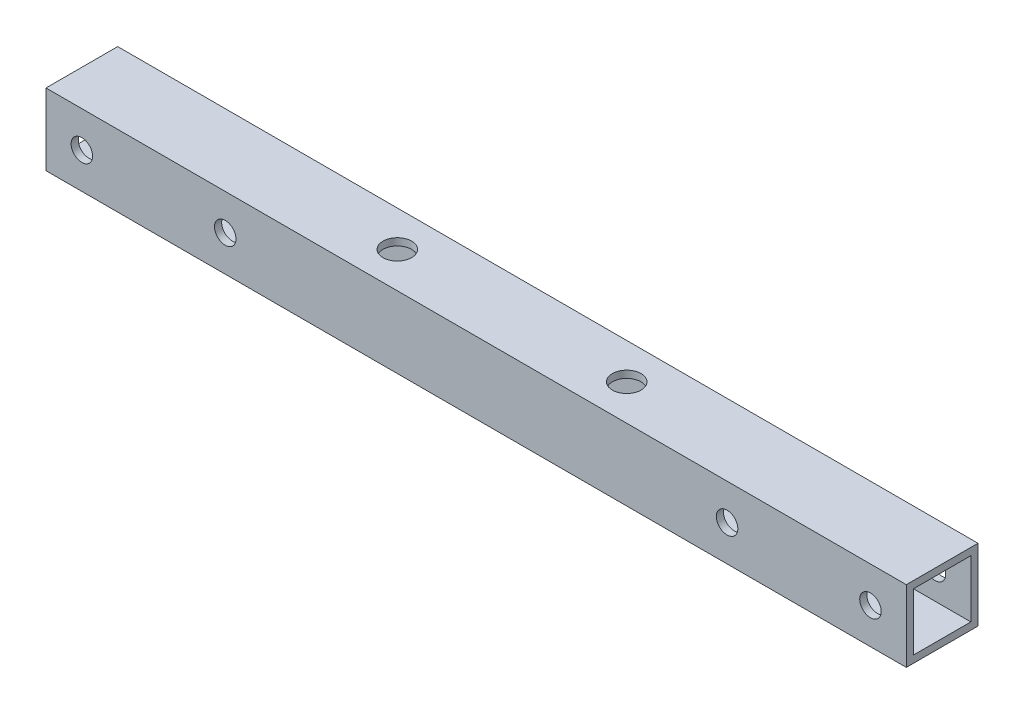
SolidWorks part; units mm, degrees
material "1060 合金"
ref_plane "正面" through (0, 0, 0) normal (0, 0, 1) x (1, 0, 0)
ref_plane "平面" through (0, 0, 0) normal (0, 1, 0) x (1, 0, 0)
ref_plane "右側面" through (0, 0, 0) normal (1, 0, 0) x (0, 0, -1)
sketch "ｽｹｯﾁ1" plane through (0, 0, 0) normal (1, 0, 0) x (0, 0, -1)
  line L1 (-5, -5) -> (5, -5)
  line L2 (-5, -5) -> (-5, 5)
  line L3 (-5, 5) -> (5, 5)
  line L4 (5, -5) -> (5, 5)
  line L5 (-5, -5) -> (5, 5) construction
  line L6 (-5, 5) -> (5, -5) construction
  point P0 (0, 0)
  dimension "D1" = 10
extrude "押し出し-薄板1" add sketch "ｽｹｯﾁ1" along normal blind 120 thin thin type one direction reverse wall 1
sketch "ｽｹｯﾁ2" plane through (0, 5, 0) normal (0, 1, 0) x (1, 0, 0)
  line L0 (0, 0) -> (120, 0) construction
  line L1 (120, 5) -> (120, -5) construction
  line L2 (60, 5) -> (60, -5) construction
  line L3 (120, 5) -> (0, 5) construction
  line L4 (120, -5) -> (0, -5) construction
  circle A0 centre (44, 0) radius 2
  circle A1 centre (76, 0) radius 2
  dimension "D1" = 32
  dimension "D2" = 4
extrude "ｶｯﾄ - 押し出し1" cut sketch "ｽｹｯﾁ2" against normal through all
sketch "ｽｹｯﾁ3" plane through (0, 0, 5) normal (0, 0, 1) x (1, 0, 0)
  line L0 (0, 0) -> (120, 0) construction
  line L1 (120, 5) -> (120, -5) construction
  line L3 (60, 5) -> (60, -5) construction
  line L4 (120, 5) -> (0, 5) construction
  line L5 (120, -5) -> (0, -5) construction
  circle A0 centre (5, 0) radius 1.5
  circle A1 centre (115, 0) radius 1.5
  circle A2 centre (25, 0) radius 1.5
  circle A3 centre (95, 0) radius 1.5
  dimension "D1" = 110
  dimension "D2" = 3
  dimension "D3" = 20
extrude "ｶｯﾄ - 押し出し2" cut sketch "ｽｹｯﾁ3" against normal through all
